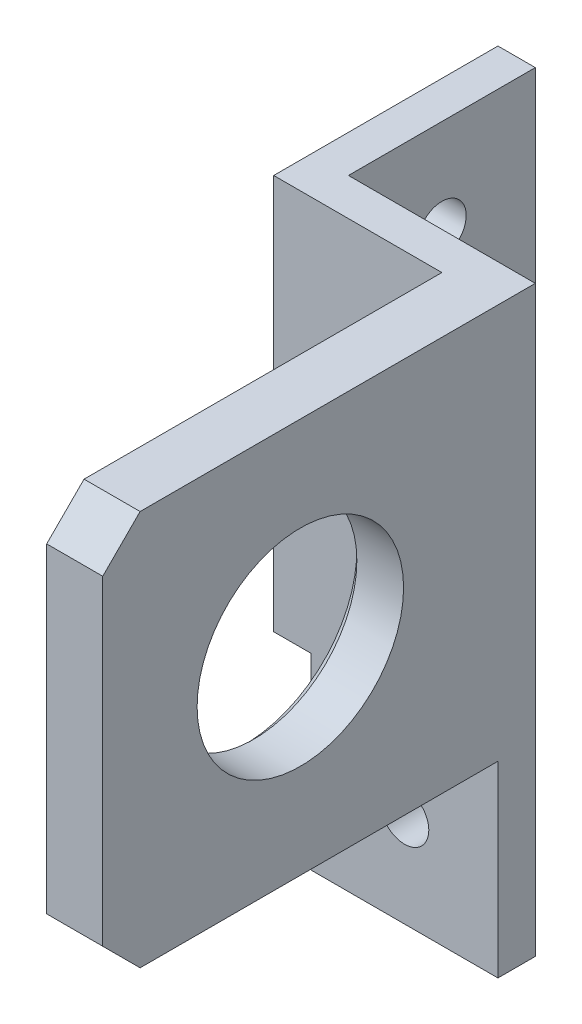
SolidWorks part; units mm, degrees
ref_plane "Přední rovina" through (0, 0, 0) normal (0, 0, 1) x (1, 0, 0)
ref_plane "Horní rovina" through (0, 0, 0) normal (0, 1, 0) x (1, 0, 0)
ref_plane "Pravá rovina" through (0, 0, 0) normal (1, 0, 0) x (0, 0, -1)
sketch "Skica2" plane through (0, 0, 0) normal (0, 0, 1) x (1, 0, 0)
  line L0 (-24.5243, -350) -> (-24.5243, 0) construction
  line L1 (-4.5243, -40) -> (-24.5243, -40)
  line L2 (-4.5243, -40) -> (-4.5243, -82.3)
  line L3 (-4.5243, -82.3) -> (-24.5243, -82.3)
  line L4 (-24.5243, -40) -> (-24.5243, -82.3)
  line L5 (-344.5243, -82.3) -> (-355.5243, -82.3) construction
extrude "Přidat vysunutím1" add sketch "Skica2" along normal blind 4
sketch "Skica3" plane through (-24.5243, 0, 0) normal (-1, 0, 0) x (0, 0, 1)
  line L0 (4, -82.3) -> (0, -82.3) construction
  line L1 (4, -40) -> (-20, -40)
  line L2 (4, -40) -> (4, -82.3)
  line L3 (4, -82.3) -> (-20, -82.3)
  line L4 (-20, -40) -> (-20, -82.3)
  line L5 (-20, -350) -> (-20, 0) construction
extrude "Přidat vysunutím2" add sketch "Skica3" along normal blind 4
sketch "Skica4" plane through (0, 0, 4) normal (0, 0, 1) x (1, 0, 0)
  line L0 (-28.5243, -82.3) -> (-4.5243, -82.3) construction
  line L1 (-10.5243, -40) -> (-4.5243, -40)
  line L2 (-10.5243, -40) -> (-10.5243, -82.3)
  line L3 (-10.5243, -82.3) -> (-4.5243, -82.3)
  line L4 (-4.5243, -40) -> (-4.5243, -82.3)
  line L5 (-4.5243, -82.3) -> (-4.5243, -40) construction
  point P9 (0, 0)
  dimension "D1" = 6
extrude "Přidat vysunutím3" add sketch "Skica4" along normal up to surface (42.3 mm away)
sketch "Skica5" plane through (-4.5243, 0, 0) normal (1, 0, 0) x (0, 0, -1)
  circle A0 centre (-25.15, -61.15) radius 11.05
  dimension "D1" = 22.1
extrude "Odebrat vysunutím1" cut sketch "Skica5" against normal blind 7
sketch "Skica7" plane through (-28.5243, 0, 0) normal (-1, 0, 0) x (0, 0, 1)
  line L0 (-20, -40) -> (-20, -82.3) construction
  line L1 (4, -40) -> (-20, -40) construction
  circle A0 centre (-10, -50) radius 2.6
  circle A1 centre (-10, -70) radius 2.6
  dimension "D3" = 5.2
  dimension "D1" = 10
  dimension "D2" = 10
  dimension "D4" = 2
extrude "Odebrat vysunutím3" cut sketch "Skica7" against normal blind 4
chamfer "Zkosení1" distance 1 angle 45 1 edges at (-10.5243, -50.1, 25.15)
sketch "Skica8" plane through (0, -82.3, 0) normal (0, -1, 0) x (1, 0, 0)
  line L0 (-28.5243, 4) -> (-10.5243, 4) construction
  line L1 (-4.5243, 0) -> (-24.5243, 0)
  line L2 (-4.5243, 0) -> (-4.5243, 4)
  line L3 (-4.5243, 4) -> (-24.5243, 4)
  line L4 (-24.5243, 0) -> (-24.5243, 4)
  point P7 (0, 0)
extrude "Přidat vysunutím4" add sketch "Skica8" along normal up to surface (20.0916 mm away)
sketch "Skica9" plane through (0, 0, 4) normal (0, 0, 1) x (1, 0, 0)
  line L0 (-24.5243, -102.3916) -> (-4.5243, -102.3916) construction
  line L1 (-4.5243, -102.3916) -> (-4.5243, -82.3) construction
  circle A0 centre (-14.5243, -92.3916) radius 2.6
  dimension "D3" = 5.2
  dimension "D1" = 10
  dimension "D2" = 10
extrude "Odebrat vysunutím4" cut sketch "Skica9" against normal blind 4
sketch "Skica10" plane through (-10.5243, 0, 0) normal (-1, 0, 0) x (0, 0, 1)
  line L0 (46.3, -44) -> (42.3, -40)
  line L1 (46.3, -40) -> (46.3, -82.3) construction
  line L2 (42.3, -40) -> (46.3, -44) construction
  line L3 (46.3, -40) -> (4, -40) construction
  line L4 (42.3, -40) -> (46.5659, -39.2593)
  line L5 (46.5659, -39.2593) -> (46.3, -44)
  line L6 (42.3, -82.3) -> (46.3, -78.3)
  line L7 (46.3, -82.3) -> (4, -82.3) construction
  line L8 (46.3, -78.3) -> (42.3, -82.3) construction
  line L9 (46.3, -78.3) -> (47.7456, -80.3)
  line L10 (47.7456, -80.3) -> (46.3, -85.4154)
  line L11 (46.3, -85.4154) -> (42.3, -82.3)
extrude "Odebrat vysunutím5" cut sketch "Skica10" against normal blind 80
